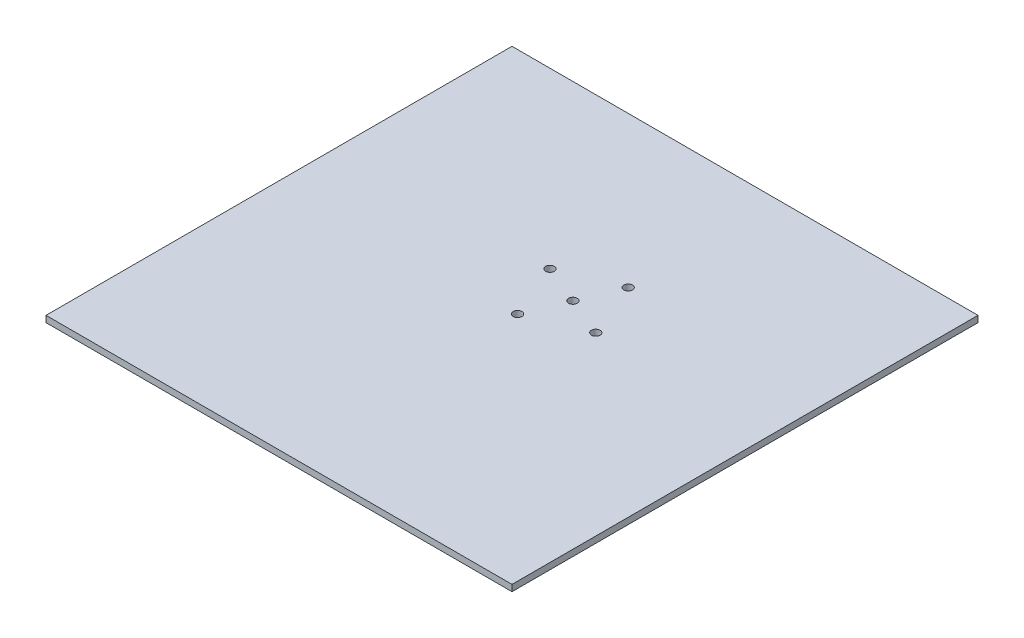
SolidWorks part; units mm, degrees
ref_plane "前视基准面" through (0, 0, 0) normal (0, 0, 1) x (1, 0, 0)
ref_plane "上视基准面" through (0, 0, 0) normal (0, 1, 0) x (1, 0, 0)
ref_plane "右视基准面" through (0, 0, 0) normal (1, 0, 0) x (0, 0, -1)
sketch "草图1" plane through (0, 0, 0) normal (0, 1, 0) x (1, 0, 0)
  line L1 (-110, 110) -> (110, 110)
  line L2 (-110, 110) -> (-110, -110)
  line L3 (-110, -110) -> (110, -110)
  line L4 (110, 110) -> (110, -110)
  line L5 (-110, 110) -> (110, -110) construction
  line L6 (-110, -110) -> (110, 110) construction
  point P0 (0, 0)
  dimension "D1" = 220
extrude "凸台-拉伸1" add sketch "草图1" along normal blind 3
sketch "草图3" plane through (0, 0, 0) normal (0, -1, 0) x (1, 0, 0)
  circle A0 centre (16.055, -38.8103) radius 2.05
  circle A1 centre (8.4098, -20.3292) radius 2.05
  circle A2 centre (26.8908, -12.684) radius 2.05
  circle A3 centre (0.7645, -1.8481) radius 2.05
  circle A4 centre (-10.0713, -27.9744) radius 2.05
  dimension "D1" = 4.1
extrude "切除-拉伸1" cut sketch "草图3" against normal through all both and the other way through all
